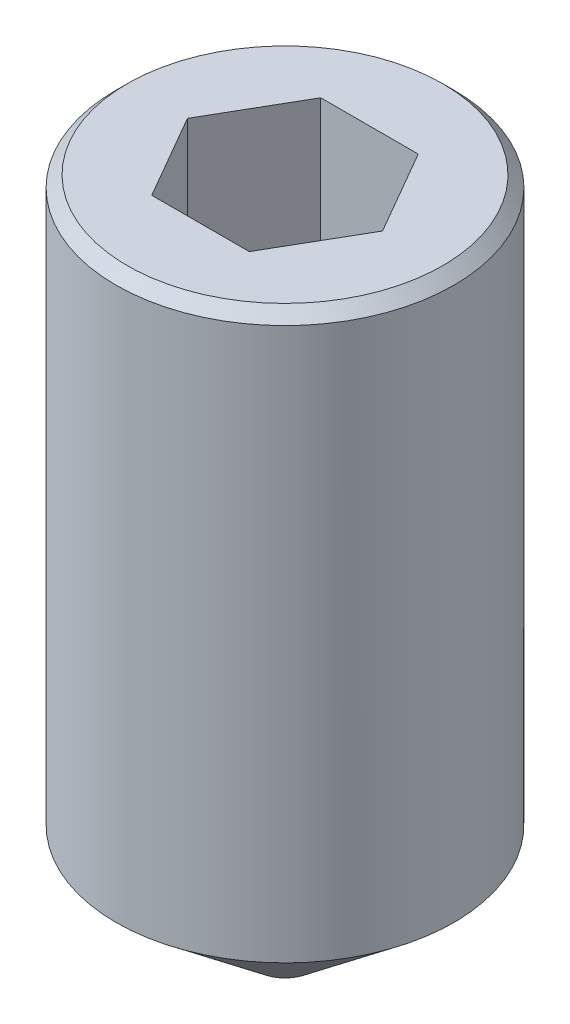
SolidWorks part; units mm, degrees
ref_plane "前视基准面" through (0, 0, 0) normal (0, 0, 1) x (1, 0, 0)
ref_plane "上视基准面" through (0, 0, 0) normal (0, 1, 0) x (1, 0, 0)
ref_plane "右视基准面" through (0, 0, 0) normal (1, 0, 0) x (0, 0, -1)
sketch "草图1" plane through (0, 0, 0) normal (0, 0, 1) x (1, 0, 0)
  line L0 (0, 0) -> (1.5, 0)
  line L1 (1.5, 0) -> (1.5, -5)
  line L2 (1.5, -5) -> (0.25, -6)
  line L3 (0, -6) -> (0, 0)
  line L4 (0, 8.7135) -> (0, -8.7135) construction
  line L5 (0.25, -6) -> (0, -6)
  point P10 (0, 0)
  dimension "D1" = 3
  dimension "D2" = 5
  dimension "D3" = 1
  dimension "D4" = 0.5
revolve "旋转1" add sketch "草图1" angle 360 about L4
sketch "草图2" plane through (0, 0, 0) normal (0, 1, 0) x (1, 0, 0)
  line L1 (-0.433, -0.75) -> (0.433, -0.75)
  line L2 (0.433, -0.75) -> (0.866, 0)
  line L3 (0.866, 0) -> (0.433, 0.75)
  line L4 (0.433, 0.75) -> (-0.433, 0.75)
  line L5 (-0.433, 0.75) -> (-0.866, 0)
  line L6 (-0.866, 0) -> (-0.433, -0.75)
  circle A0 centre (0, 0) radius 0.75 construction
  dimension "D1" = 1.5
extrude "切除-拉伸1" cut sketch "草图2" against normal blind 1.5
chamfer "倒角1" distance 0.1 angle 45 1 edges at (0, 0, 1.5)
